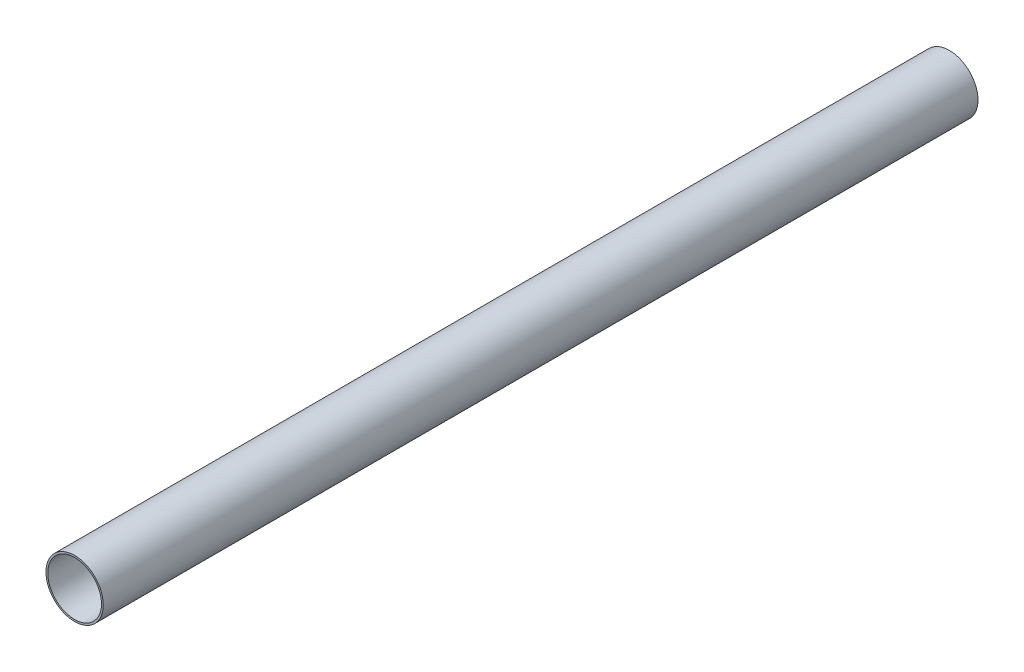
SolidWorks part; units mm, degrees
material "Zoltek Panex 33"
ref_plane "Front Plane" through (0, 0, 0) normal (0, 0, 1) x (1, 0, 0)
ref_plane "Top Plane" through (0, 0, 0) normal (0, 1, 0) x (1, 0, 0)
ref_plane "Right Plane" through (0, 0, 0) normal (1, 0, 0) x (0, 0, -1)
sketch "Sketch1" plane through (0, 0, 0) normal (0, 0, 1) x (1, 0, 0)
  circle A0 centre (0, 0) radius 12.7
  circle A1 centre (0, 0) radius 11.9062
  dimension "D1" = 25.4
  dimension "D2" = 0.7937
extrude "Boss-Extrude1" add sketch "Sketch1" along normal blind 387.62
